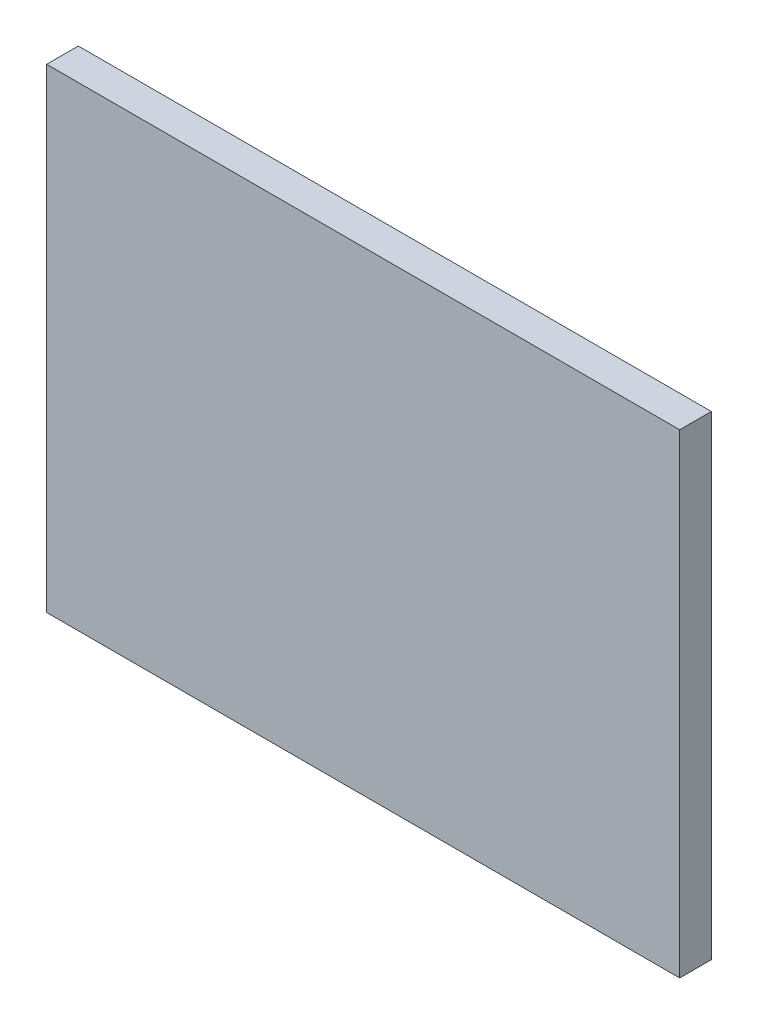
SolidWorks part; units mm, degrees
ref_plane "Ebene vorne" through (0, 0, 0) normal (0, 0, 1) x (1, 0, 0)
ref_plane "Ebene oben" through (0, 0, 0) normal (0, 1, 0) x (1, 0, 0)
ref_plane "Ebene rechts" through (0, 0, 0) normal (1, 0, 0) x (0, 0, -1)
sketch "Skizze1" plane through (0, 0, 0) normal (0, 0, 1) x (1, 0, 0)
  line L1 (-100, 75) -> (100, 75)
  line L2 (-100, 75) -> (-100, -75)
  line L3 (-100, -75) -> (100, -75)
  line L4 (100, 75) -> (100, -75)
  line L5 (-100, 75) -> (100, -75) construction
  line L6 (-100, -75) -> (100, 75) construction
  point P0 (0, 0)
  dimension "D1" = 200
  dimension "D2" = 150
extrude "Aufsatz-Linear austragen1" add sketch "Skizze1" along normal blind 10
sketch "Skizze2" plane through (0, 0, 0) normal (0, 0, -1) x (-1, 0, 0)
  circle A0 centre (0, 0) radius 2.5
  circle A1 centre (28, 0) radius 2.5
  dimension "D1" = 28
extrude "Aufsatz-Linear austragen2" add sketch "Skizze2" along normal blind 10
